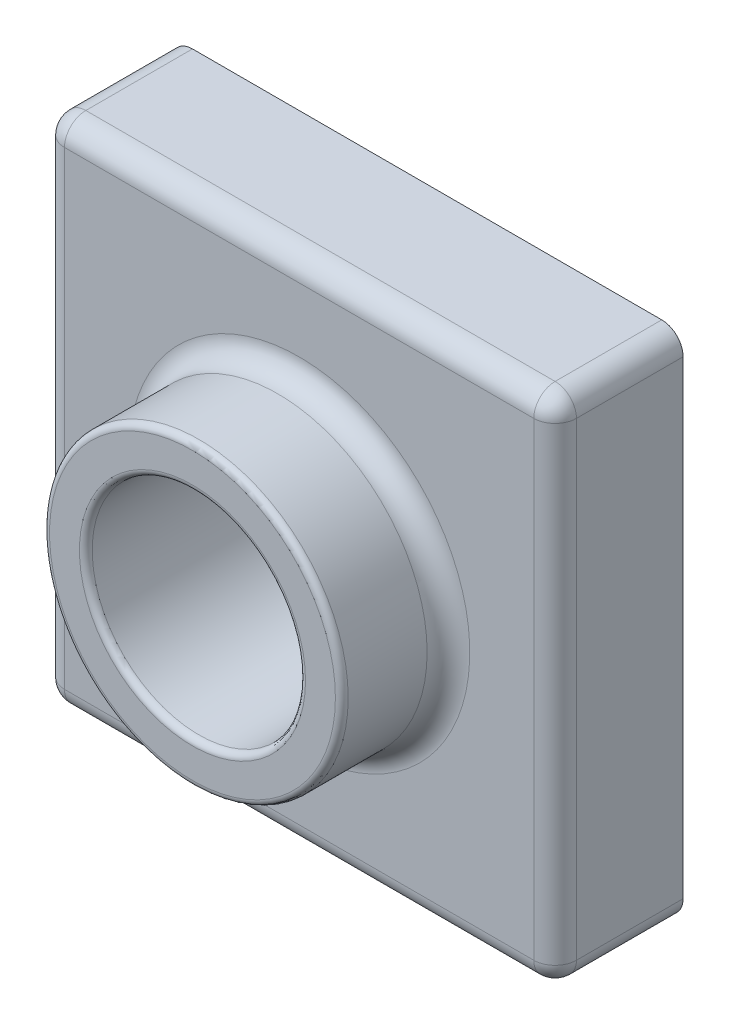
SolidWorks part; units mm, degrees
ref_plane "Front Plane" through (0, 0, 0) normal (0, 0, 1) x (1, 0, 0)
ref_plane "Top Plane" through (0, 0, 0) normal (0, 1, 0) x (1, 0, 0)
ref_plane "Right Plane" through (0, 0, 0) normal (1, 0, 0) x (0, 0, -1)
other "Configuration Table"
sketch "Sketch2" plane through (0, 0, 0) normal (0, 0, 1) x (1, 0, 0)
  line L1 (0, 0) -> (120, 0)
  line L2 (0, 0) -> (0, 120)
  line L3 (0, 120) -> (120, 120)
  line L4 (120, 0) -> (120, 120)
  dimension "D1" = 120
  dimension "D2" = 120
extrude "Boss-Extrude1" add sketch "Sketch2" along normal blind 30
sketch "Sketch4" plane through (0, 0, 30) normal (0, 0, 1) x (1, 0, 0)
  line L0 (120, 120) -> (0, 120) construction
  line L1 (0, 120) -> (0, 0) construction
  circle A0 centre (60, 60) radius 35
  dimension "D1" = 60
  dimension "D3" = 70
  dimension "D2" = 60
extrude "Boss-Extrude2" add sketch "Sketch4" along normal blind 25
sketch "Sketch6" plane through (0, 0, 55) normal (0, 0, 1) x (1, 0, 0)
  circle A0 centre (60, 60) radius 25
  dimension "D1" = 50
extrude "Cut-Extrude1" cut sketch "Sketch6" against normal through all
fillet "Fillet1" radius 5 9 edges at (25, 60, 30) (60, 120, 30) (120, 60, 30) (60, 0, 30) (0, 60, 30) (0, 0, 15) (120, 0, 15) (120, 120, 15) (0, 120, 15)
fillet "Fillet2" radius 1.5 2 edges at (95, 60, 55) (85, 60, 55)
